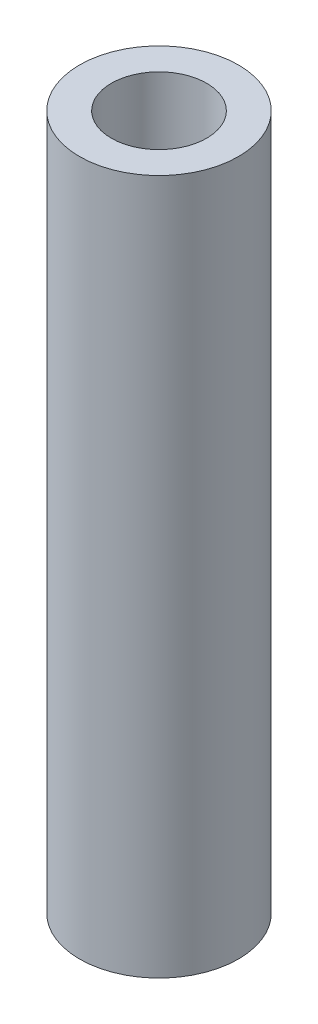
SolidWorks part; units mm, degrees
ref_plane "前视基准面" through (0, 0, 0) normal (0, 0, 1) x (1, 0, 0)
ref_plane "上视基准面" through (0, 0, 0) normal (0, 1, 0) x (1, 0, 0)
ref_plane "右视基准面" through (0, 0, 0) normal (1, 0, 0) x (0, 0, -1)
other "Configuration Table"
sketch "草图1" plane through (0, 0, 0) normal (0, 1, 0) x (1, 0, 0)
  circle A0 centre (0, 0) radius 2.4
  circle A1 centre (0, 0) radius 4
  dimension "D1" = 4.8
  dimension "D2" = 8
extrude "凸台-拉伸1" add sketch "草图1" along normal blind 35
